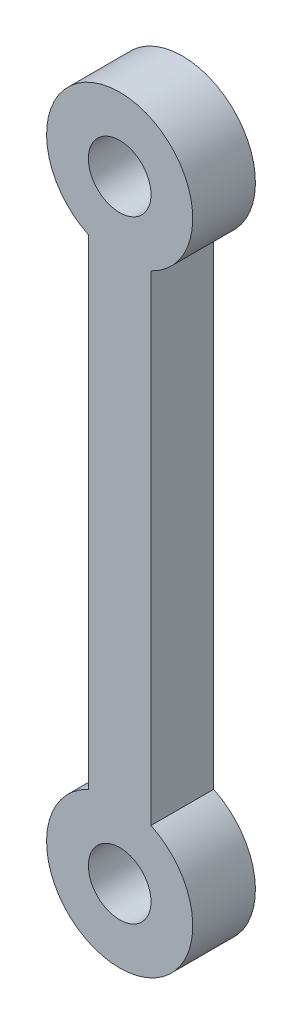
SolidWorks part; units mm, degrees
ref_plane "Piano frontale" through (0, 0, 0) normal (0, 0, 1) x (1, 0, 0)
ref_plane "Piano superiore" through (0, 0, 0) normal (0, 1, 0) x (1, 0, 0)
ref_plane "Piano destro" through (0, 0, 0) normal (1, 0, 0) x (0, 0, -1)
sketch "Schizzo2" plane through (0, 0, 0) normal (0, 0, 1) x (1, 0, 0)
  line L0 (-36.1111, -20.5665) -> (-36.1111, -27.5665)
  line L1 (-34.1111, -27.5665) -> (-34.1111, -50.5665)
  line L2 (-34.1111, -50.5665) -> (-36.1111, -50.5665)
  line L3 (-36.1111, -50.5665) -> (-36.1111, -57.5665)
  line L4 (-36.1111, -57.5665) -> (-29.1111, -57.5665)
  line L5 (-29.1111, -57.5665) -> (-29.1111, -50.5665)
  line L6 (-29.1111, -50.5665) -> (-31.1111, -50.5665)
  line L7 (-31.1111, -50.5665) -> (-31.1111, -27.5665)
  line L8 (-31.1111, -27.5665) -> (-29.1111, -27.5665)
  line L9 (-29.1111, -27.5665) -> (-29.1111, -20.5665)
  line L10 (-29.1111, -20.5665) -> (-36.1111, -20.5665)
  line L11 (-36.1111, -27.5665) -> (-34.1111, -27.5665)
  line L12 (-32.6111, -20.5665) -> (-32.6111, -57.5665) construction
  line L13 (-36.0948, -24.0665) -> (-29.1111, -24.0665) construction
  line L14 (-36.1111, -54.0665) -> (-29.1274, -54.0665) construction
  circle A0 centre (-32.6111, -24.4042) radius 3.5
  circle A1 centre (-32.6111, -53.7288) radius 3.5
  point P23 (-32.6111, -20.5665)
  point P25 (-29.1111, -24.0665)
  point P26 (-36.1111, -54.2165)
  point P27 (-32.6111, -57.5665)
  point P28 (-29.1274, -54.0665)
  point P29 (-31.1111, -27.5665)
  point P30 (-34.1111, -27.5665)
  point P31 (-31.1111, -50.5665)
  point P32 (-29.1274, -54.0665)
  point P33 (-36.1111, -54.0665)
  point P34 (-34.1111, -50.5665)
  point P35 (-31.1111, -50.5665)
  point P37 (-29.1111, -24.0665)
  point P40 (-34.1111, -50.5665)
  dimension "D7" = 7
  dimension "D8" = 7
  dimension "D9" = 3.5
  dimension "D1" = 37
  dimension "D2" = 3
  dimension "D3" = 7
  dimension "D4" = 7
  dimension "D5" = 7
  dimension "D6" = 3.5
extrude "Estrusione-Estrusione2" add sketch "Schizzo2" along normal blind 3 contours A0 L0 | A1 L7 A0 L1 | A1 L3
sketch "Schizzo3" plane through (0, 0, 0) normal (0, 0, 1) x (1, 0, 0)
  line L0 (-32.6111, -20.9042) -> (-32.6111, -57.2288) construction
  line L1 (-36.1111, -24.4042) -> (-29.1111, -24.4042) construction
  line L2 (-36.1111, -53.7288) -> (-29.1111, -53.7288) construction
  arc A0 (-31.1111, -27.5665) -> (-34.1111, -27.5665) centre (-32.6111, -24.4042) ccw construction
  arc A1 (-34.1111, -50.5665) -> (-31.1111, -50.5665) centre (-32.6111, -53.7288) ccw construction
  circle A2 centre (-32.6111, -24.4042) radius 1.5
  circle A3 centre (-32.6111, -53.7288) radius 1.5
  dimension "D1" = 3
  dimension "D2" = 3
extrude "Taglio-Estrusione7" cut sketch "Schizzo3" against normal through all from surface at 3 starting at face at (-32.6111, -39.0665, 3)
